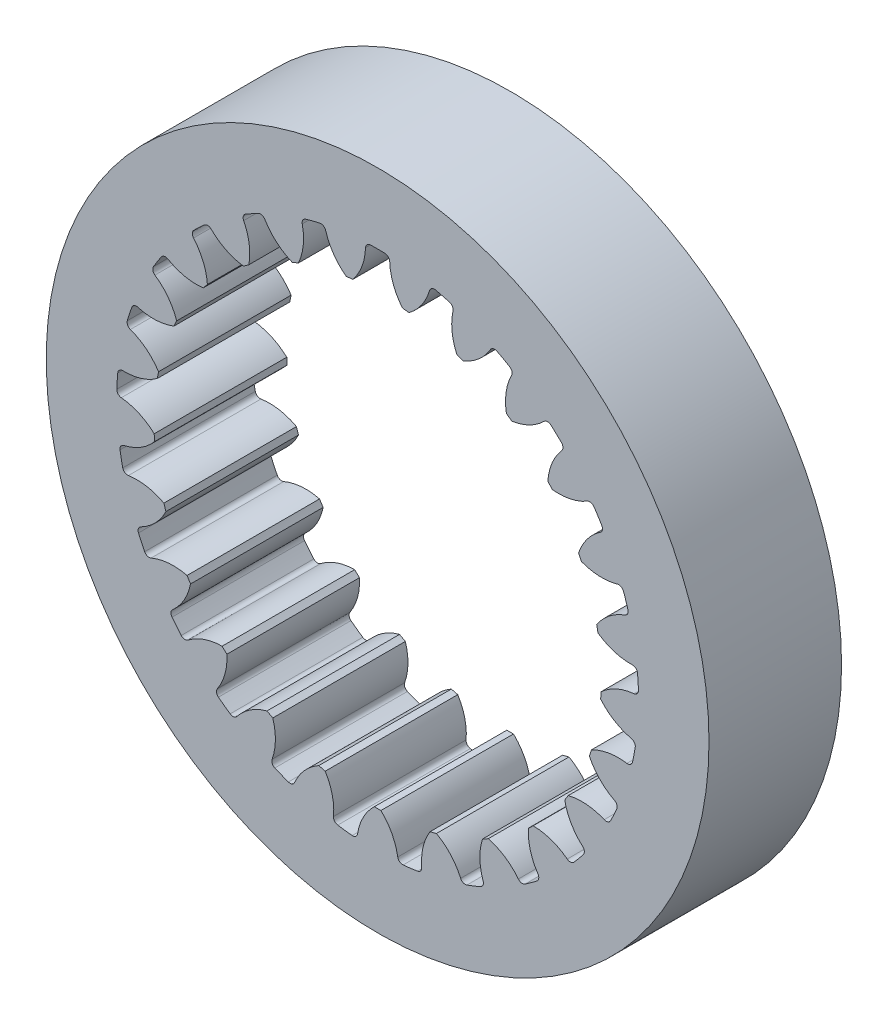
SolidWorks part; units mm, degrees
ref_plane "Спереди" through (0, 0, 0) normal (0, 0, 1) x (1, 0, 0)
ref_plane "Сверху" through (0, 0, 0) normal (0, 1, 0) x (1, 0, 0)
ref_plane "Справа" through (0, 0, 0) normal (1, 0, 0) x (0, 0, -1)
sketch "Эскиз1" plane through (0, 0, 0) normal (0, 0, 1) x (1, 0, 0)
  circle A0 centre (0, 0) radius 16.875
  circle A1 centre (0, 0) radius 18.125
  circle A2 centre (0, 0) radius 19.6875
  circle A3 centre (0, 0) radius 25
  dimension "D1" = 33.75
  dimension "D2" = 36.25
  dimension "D4" = 50
  dimension "D3" = 2.8125
extrude "Бобышка-Вытянуть1" add sketch "Эскиз1" along normal blind 10 contours A3
sketch "Эскиз2" plane through (0, 0, 0) normal (0, 0, 1) x (1, 0, 0)
  line L0 (0, 0) -> (0, 25) construction
  line L1 (0.9144, 19.6663) -> (0, 0) construction
  line L2 (1.1381, 18.0892) -> (-1.1381, 18.0892) construction
  line L3 (-0.5664, 23.0933) -> (3.9139, 9.94) construction
  line L4 (-1.1381, 18.0892) -> (-3.3963, 17.804) construction
  line L5 (0, 0) -> (-3.452, 27.3256) construction
  circle A0 centre (0, 0) radius 25 construction
  circle A1 centre (0, 0) radius 16.875 construction
  circle A2 centre (0, 0) radius 16.875
  arc A3 (3.9294, 15.381) -> (0.9144, 19.6663) centre (5.185, 19.4677) cw
  circle A4 centre (0, 0) radius 19.6875 construction
  arc A5 (-3.9294, 15.381) -> (-0.9144, 19.6663) centre (-5.185, 19.4677) ccw
  circle A6 centre (0, 0) radius 18.125 construction
  circle A7 centre (0, 0) radius 15.875
  circle A8 centre (0, 0) radius 19.6875
  point P16 (2.0081, 15.7109)
  dimension "D1" = 18.81
  dimension "D3" = 7.2
  dimension "D2" = 1
extrude "Вырез-Вытянуть2" cut sketch "Эскиз2" against normal through all and the other way through all contours A3 A8 A5 A2 | A7 A3 A2 A5 | A7 A5 A2 A3 | A7
fillet "Скругление1" radius 0.375 2 edges at (0.9144, 19.6663, 5) (-0.9144, 19.6663, 5)
pattern_circular "Круговой массив1" count 25 over 360 about axis through (0, 0, 0) along (0, 0, 1) of "Вырез-Вытянуть2", "Скругление1"
equation "\"модуль\"= 1.25"
equation "\"число зубьев\"= 25"
equation "\"ширина\"= 10"
equation "\"внешний диаметр\"= 50"
equation "\"скругление\"= \"модуль\" * 0.3"
equation "\"D1@Эскиз1\"=(\"число зубьев\"+2)*\"модуль\""
equation "\"D2@Эскиз1\"=2*(\"число зубьев\"+2)*\"модуль\"-\"число зубьев\"*\"модуль\""
equation "\"D3@Эскиз1\"= \"модуль\"*if(\"модуль\">=1.25, 2.25, 2.4)"
equation "\"D4@Эскиз1\"=\"внешний диаметр\""
equation "\"D3@Эскиз2\"=180/\"число зубьев\""
equation "\"D1@Скругление1\"=\"скругление\""
equation "\"D1@Круговой массив1\"= \"число зубьев\""
